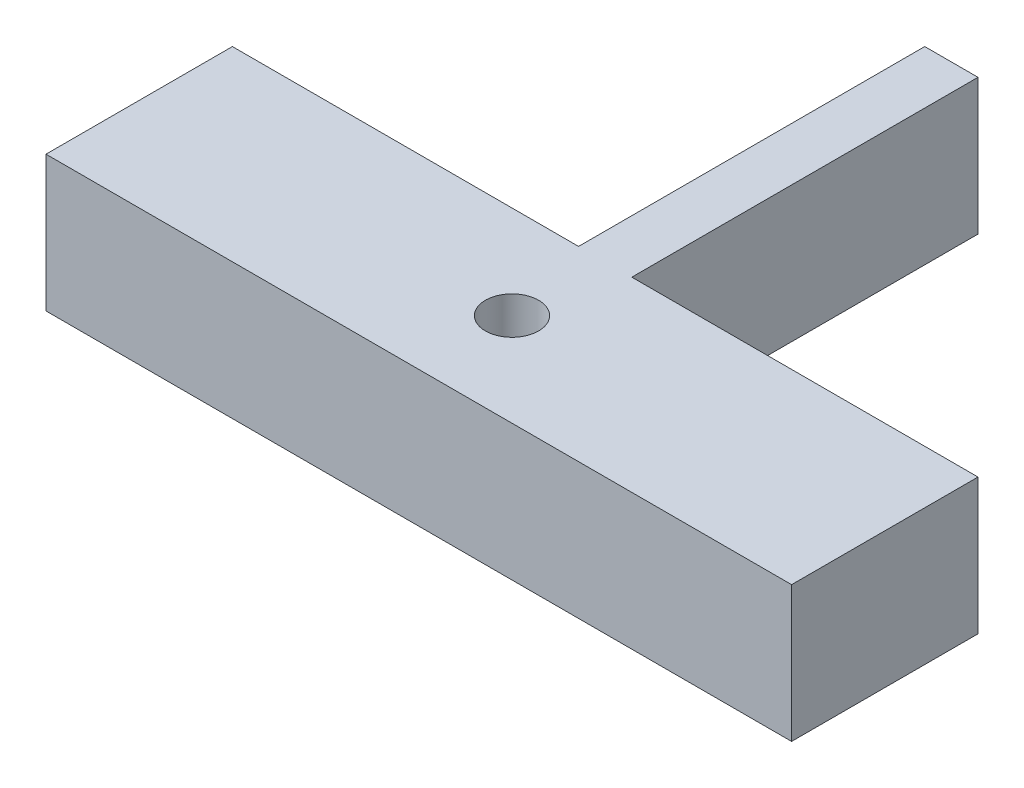
SolidWorks part; units mm, degrees
ref_plane "Спереди" through (0, 0, 0) normal (0, 0, 1) x (1, 0, 0)
ref_plane "Сверху" through (0, 0, 0) normal (0, 1, 0) x (1, 0, 0)
ref_plane "Справа" through (0, 0, 0) normal (1, 0, 0) x (0, 0, -1)
sketch "Эскиз1" plane through (0, 0, 0) normal (0, 1, 0) x (1, 0, 0)
  line L0 (0, 100) -> (0, -100) construction
  line L1 (10, 100) -> (-10, 100)
  line L2 (-10, 100) -> (-10, -30)
  line L3 (-10, -30) -> (-140, -30)
  line L4 (-140, -30) -> (-140, -100)
  line L5 (-140, -100) -> (140, -100)
  line L6 (140, -30) -> (140, -100)
  line L7 (10, -30) -> (140, -30)
  line L8 (10, 100) -> (10, -30)
  point P10 (0, -100)
  point P13 (0, 100)
  dimension "D1" = 20
  dimension "D2" = 130
  dimension "D3" = 130
  dimension "D4" = 70
extrude "Бобышка-Вытянуть1" add sketch "Эскиз1" along normal mid plane 51
sketch "Эскиз2" plane through (0, 0, 0) normal (0, 1, 0) x (1, 0, 0)
  line L0 (0, 23.6135) -> (0, -119.2266) construction
  line L1 (-140, -65) -> (140, -65) construction
  line L2 (-140, -30) -> (-140, -100) construction
  line L3 (140, -100) -> (140, -30) construction
  circle A0 centre (0, -65) radius 10
  dimension "D1" = 20
extrude "Вырез-Вытянуть1" cut sketch "Эскиз2" against normal through all and the other way through all
